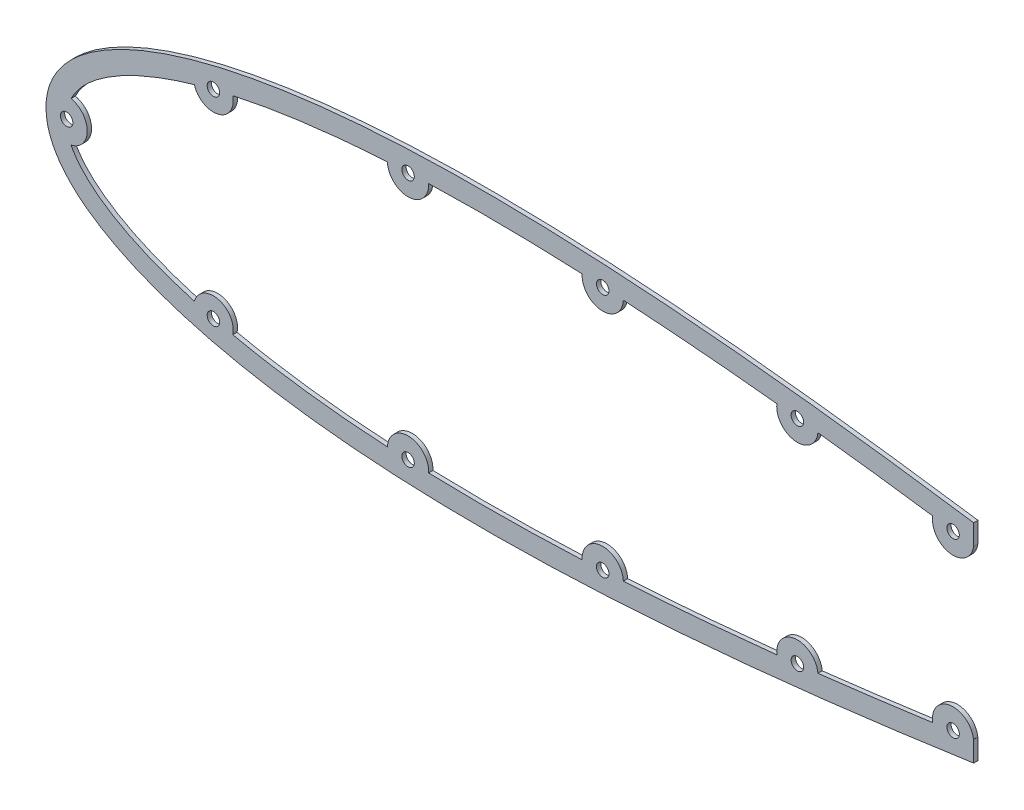
SolidWorks part; units mm, degrees
material "Silicon Rubber"
ref_plane "Front Plane" through (0, 0, 0) normal (0, 0, 1) x (1, 0, 0)
ref_plane "Top Plane" through (0, 0, 0) normal (0, 1, 0) x (1, 0, 0)
ref_plane "Right Plane" through (0, 0, 0) normal (1, 0, 0) x (0, 0, -1)
sketch "Sketch2" plane through (0, 0, 0) normal (0, 0, 1) x (1, 0, 0)
  line L0 (68.2014, -26.7339) -> (68.2014, -21.4783)
  line L1 (68.2014, -21.4783) -> (68.1599, -21.4844)
  line L2 (68.1599, 21.4844) -> (68.2014, 21.4783)
  line L3 (68.2014, 21.4783) -> (68.2014, 26.7339)
  line L6 (68.1014, 21.5941) -> (68.1014, 26.6475)
  line L7 (68.0724, 21.5983) -> (68.1014, 21.5941)
  line L8 (68.1014, -21.5941) -> (68.0724, -21.5983)
  line L12 (68.1014, -26.6475) -> (68.1014, -21.5941)
  line L13 (68.1014, 21.5941) -> (68.1014, 26.6475)
  line L14 (68.0724, 21.5983) -> (68.1014, 21.5941)
  line L16 (68.1014, -21.5941) -> (68.0724, -21.5983)
  line L18 (68.1014, -26.6475) -> (68.1014, -21.5941)
  circle A0 centre (62.9014, 22.1461) radius 1.6 construction
  circle A1 centre (22.9014, 27.2583) radius 1.6 construction
  circle A2 centre (-27.0986, 31.4546) radius 1.6 construction
  circle A3 centre (-77.0986, 31.8817) radius 1.6 construction
  circle A4 centre (-127.0986, 25.5249) radius 1.6 construction
  circle A5 centre (-164.8, 0) radius 1.6 construction
  circle A6 centre (-77.0986, -31.8817) radius 1.6 construction
  circle A7 centre (-27.0986, -31.4546) radius 1.6 construction
  circle A8 centre (22.9014, -27.2583) radius 1.6 construction
  circle A9 centre (62.9014, -22.1461) radius 1.6 construction
  circle A10 centre (-127.0986, -25.5249) radius 1.6 construction
  arc A11 (57.7843, 23.0714) -> (68.0724, 21.5983) centre (62.9014, 22.1461) ccw
  arc A12 (17.7571, 28.0176) -> (28.087, 26.8723) centre (22.9014, 27.2583) ccw
  arc A13 (-32.2789, 31.9078) -> (-21.8995, 31.3623) centre (-27.0986, 31.4546) ccw
  arc A14 (-82.2982, 31.8126) -> (-71.9139, 32.2795) centre (-77.0986, 31.8817) ccw
  arc A16 (-131.9264, 24.2269) -> (-122.2317, 26.6674) centre (-127.0986, 25.5249) ccw
  arc A18 (-163.7985, -5.1026) -> (-163.7985, 5.1026) centre (-164.8, 0) ccw
  arc A20 (-122.2317, -26.6674) -> (-131.9264, -24.2269) centre (-127.0986, -25.5249) ccw
  arc A22 (-71.9139, -32.2795) -> (-82.2982, -31.8126) centre (-77.0986, -31.8817) ccw
  arc A24 (-21.8995, -31.3623) -> (-32.2789, -31.9078) centre (-27.0986, -31.4546) ccw
  arc A39 (28.087, -26.8723) -> (17.7571, -28.0176) centre (22.9014, -27.2583) ccw
  arc A40 (68.0724, -21.5983) -> (57.7843, -23.0714) centre (62.9014, -22.1461) ccw
  arc A41 (57.7843, 23.0714) -> (68.0724, 21.5983) centre (62.9014, 22.1461) ccw
  arc A42 (17.7571, 28.0176) -> (28.087, 26.8723) centre (22.9014, 27.2583) ccw
  arc A43 (-32.2789, 31.9078) -> (-21.8995, 31.3623) centre (-27.0986, 31.4546) ccw
  arc A44 (-82.2982, 31.8126) -> (-71.9139, 32.2795) centre (-77.0986, 31.8817) ccw
  arc A45 (-131.9264, 24.2269) -> (-122.2317, 26.6674) centre (-127.0986, 25.5249) ccw
  arc A46 (-163.7985, -5.1026) -> (-163.7985, 5.1026) centre (-164.8, 0) ccw
  arc A47 (-122.2317, -26.6674) -> (-131.9264, -24.2269) centre (-127.0986, -25.5249) ccw
  arc A48 (-71.9139, -32.2795) -> (-82.2982, -31.8126) centre (-77.0986, -31.8817) ccw
  arc A49 (-21.8995, -31.3623) -> (-32.2789, -31.9078) centre (-27.0986, -31.4546) ccw
  arc A52 (28.087, -26.8723) -> (17.7571, -28.0176) centre (22.9014, -27.2583) ccw
  arc A54 (68.0724, -21.5983) -> (57.7843, -23.0714) centre (62.9014, -22.1461) ccw
  circle A56 centre (62.9014, 22.1461) radius 1.6
  circle A58 centre (22.9014, 27.2583) radius 1.6
  circle A60 centre (-27.0986, 31.4546) radius 1.6
  circle A65 centre (-77.0986, 31.8817) radius 1.6
  circle A66 centre (-127.0986, 25.5249) radius 1.6
  circle A67 centre (-164.8, 0) radius 1.6
  circle A68 centre (-77.0986, -31.8817) radius 1.6
  circle A69 centre (-27.0986, -31.4546) radius 1.6
  circle A70 centre (22.9014, -27.2583) radius 1.6
  circle A71 centre (62.9014, -22.1461) radius 1.6
  circle A72 centre (-127.0986, -25.5249) radius 1.6
  arc A73 (68.1599, -21.4844) -> (57.6684, -22.9866) centre (62.9014, -22.1461) ccw
  arc A74 (28.178, -26.7611) -> (17.644, -27.929) centre (22.9014, -27.2583) ccw
  arc A75 (-21.8024, -31.2563) -> (-32.3865, -31.8125) centre (-27.0986, -31.4546) ccw
  arc A76 (-71.8072, -32.1828) -> (-82.3958, -31.7067) centre (-77.0986, -31.8817) ccw
  arc A77 (-122.1122, -26.5912) -> (-131.9956, -24.1029) centre (-127.0986, -25.5249) ccw
  arc A78 (-163.6523, -5.1742) -> (-163.6523, 5.1742) centre (-164.8, 0) ccw
  arc A79 (-131.9956, 24.1029) -> (-122.1122, 26.5912) centre (-127.0986, 25.5249) ccw
  arc A80 (-82.3958, 31.7067) -> (-71.8072, 32.1828) centre (-77.0986, 31.8817) ccw
  arc A105 (-32.3865, 31.8125) -> (-21.8024, 31.2563) centre (-27.0986, 31.4546) ccw
  arc A106 (17.644, 27.929) -> (28.178, 26.7611) centre (22.9014, 27.2583) ccw
  arc A107 (57.6684, 22.9866) -> (68.1599, 21.4844) centre (62.9014, 22.1461) ccw
  spline S0 degree 1 poles (68.2014, 26.7339) (-170.1, 0) knots 0 0 1 1 construction
  spline S1 degree 1 poles (-170.1, 0) (68.2014, -26.7339) knots 0 0 1 1 construction
  spline S2 degree 1 poles (57.6684, -22.9866) (28.178, -26.7611) knots 0 0 1 1 construction
  spline S3 degree 1 poles (17.644, -27.929) (-21.8024, -31.2563) knots 0 0 1 1 construction
  spline S4 degree 1 poles (-32.3865, -31.8125) (-71.8072, -32.1828) knots 0 0 1 1 construction
  spline S5 degree 1 poles (-82.3958, -31.7067) (-122.1122, -26.5912) knots 0 0 1 1 construction
  spline S6 degree 1 poles (-131.9956, -24.1029) (-163.6523, -5.1742) knots 0 0 1 1 construction
  spline S7 degree 1 poles (-163.6523, 5.1742) (-131.9956, 24.1029) knots 0 0 1 1 construction
  spline S8 degree 1 poles (-122.1122, 26.5912) (-82.3958, 31.7067) knots 0 0 1 1 construction
  spline S9 degree 1 poles (-71.8072, 32.1828) (-32.3865, 31.8125) knots 0 0 1 1 construction
  spline S10 degree 1 poles (-21.8024, 31.2563) (17.644, 27.929) knots 0 0 1 1 construction
  spline S11 degree 1 poles (28.178, 26.7611) (57.6684, 22.9866) knots 0 0 1 1 construction
  spline S13 degree 3 poles (-842.1181, -1671.7155) (-666.8136, -29.7436) (-299.6609, 70.7294) (451.6225, -29.366) (859.6621, -263.4671) (-1750.034, 876.0193) knots -3.144259 -3.144259 -3.144259 -3.144259 0.860716 0.922196 5.547029 5.547029 5.547029 5.547029 only from (28.087, 26.8723) to (57.7843, 23.0714)
  spline S14 degree 3 poles (-801.262, -1742.9904) (-608.4086, -55.3942) (138.9892, 217.5077) (846.5588, -333.1109) (874.3091, 1643.1183) knots -2.784932 -2.784932 -2.784932 -2.784932 0.737757 5.645129 5.645129 5.645129 5.645129 only from (-21.8995, 31.3623) to (17.7571, 28.0176)
  spline S15 degree 3 poles (-291.0162, -1916.8032) (-507.1608, -118.9354) (34.6459, 253.136) (621.4934, -288.9416) (405.8213, 1893.2388) knots -2.162015 -2.162015 -2.162015 -2.162015 0.491838 4.302613 4.302613 4.302613 4.302613 only from (-71.9139, 32.2795) to (-32.2789, 31.9078)
  spline S16 degree 3 poles (741.1533, -1760.707) (-343.2115, -150.34) (-241.253, 13.975) (186.8439, 63.9274) (527.7556, -277.064) (56.5333, 1961.8797) knots -1.314597 -1.314597 -1.314597 -1.314597 0.245919 0.368878 3.687915 3.687915 3.687915 3.687915 only from (-122.2317, 26.6674) to (-82.2982, 31.8126)
  spline S17 degree 3 poles (1723.4477, -655.8326) (258.0308, -164.7434) (-207.3618, -48.8694) (-159.9742, 10.6557) (-154.2388, 14.9829) (-147.6638, 18.5471) (-140.6029, 21.4867) (12.7833, 72.1997) (283.1196, -141.398) (-1275.2751, 1653.5581) knots -0.974835 -0.974835 -0.974835 -0.974835 0.03074 0.06148 0.09222 0.122959 0.153699 0.184439 2.046029 2.046029 2.046029 2.046029 only from (-163.7985, 5.1026) to (-131.9264, 24.2269)
  spline S18 degree 3 poles (-1275.2616, -1653.5425) (283.118, 141.3968) (12.7829, -72.1996) (-140.6029, -21.4867) (-147.6638, -18.5471) (-154.2388, -14.9829) (-159.9742, -10.6557) (-207.3614, 48.8689) (258.0229, 164.7415) (1723.4095, 655.8198) knots -1.062348 -1.062348 -1.062348 -1.062348 0.799237 0.829976 0.860716 0.891456 0.922196 0.952936 1.958502 1.958502 1.958502 1.958502 only from (-131.9264, -24.2269) to (-163.7985, -5.1026)
  spline S19 degree 3 poles (56.5306, -1961.8927) (527.7568, 277.0653) (186.8444, -63.9275) (-241.253, -13.975) (-343.2116, 150.34) (741.1538, 1760.7078) knots -2.704246 -2.704246 -2.704246 -2.704246 0.614797 0.737757 2.298273 2.298273 2.298273 2.298273 only from (-82.2982, -31.8126) to (-122.2317, -26.6674)
  spline S20 degree 3 poles (405.8239, -1893.2123) (621.4906, 288.939) (34.6482, -253.1318) (-507.1541, 118.9308) (-291.0259, 1916.7219) knots -3.318922 -3.318922 -3.318922 -3.318922 0.491838 3.145651 3.145651 3.145651 3.145651 only from (-32.2789, -31.9078) to (-71.9139, -32.2795)
  spline S21 degree 3 poles (874.3087, -1643.0904) (846.555, 333.1079) (138.9897, -217.5049) (-608.4031, 55.3922) (-801.257, 1742.9458) knots -4.66143 -4.66143 -4.66143 -4.66143 0.245919 3.768577 3.768577 3.768577 3.768577 only from (17.7571, -28.0176) to (-21.8995, -31.3623)
  spline S22 degree 3 poles (-1750.0783, -876.0387) (859.6666, 263.4697) (451.6248, 29.3663) (-299.6602, -70.7293) (-666.8122, 29.7432) (-842.1171, 1671.7055) knots -4.563379 -4.563379 -4.563379 -4.563379 0.06148 0.122959 4.127926 4.127926 4.127926 4.127926 only from (57.7843, -23.0714) to (28.087, -26.8723)
  spline S23 degree 3 poles (708.7122, -1786.7537) (26.0228, 147.1611) (-186.9064, 41.2677) (-168.2655, -7.6563) (-166.1256, -10.9895) (-163.4817, -13.9306) (-160.4992, -16.5204) (-156.2088, -19.5733) (-150.4451, -22.7629) (-143.1818, -25.8606) (-135.7072, -28.4002) (-128.0976, -30.4933) (-120.3969, -32.2192) (-112.6334, -33.6326) (-104.8261, -34.778) (-96.9881, -35.6886) (-89.1288, -36.3914) (-81.2552, -36.9087) (-73.3723, -37.259) (-65.4842, -37.4585) (-57.5937, -37.5209) (-49.7032, -37.4581) (-39.1846, -37.2223) (-26.0439, -36.6653) (-10.2939, -35.6417) (5.4338, -34.3131) (21.1378, -32.722) (36.8174, -30.901) (531.6613, 33.0393) (986.8564, 360.6878) (1492.0432, -1113.8011) knots -0.00686 -0.00686 -0.00686 -0.00686 0.369162 0.379176 0.389189 0.399202 0.409216 0.419229 0.439256 0.459282 0.479309 0.499335 0.519362 0.539388 0.559415 0.579442 0.599468 0.619495 0.639521 0.659548 0.679575 0.699601 0.719628 0.759681 0.799734 0.839787 0.879841 0.919894 0.959947 4.677847 4.677847 4.677847 4.677847 only from (-170, 0) to (68.1014, -26.6475)
  spline S24 degree 3 poles (1492.0395, 1113.7903) (986.8542, -360.6862) (531.6601, -33.0392) (36.8174, 30.901) (21.1378, 32.722) (5.4338, 34.3131) (-10.2939, 35.6417) (-26.0439, 36.6653) (-39.1846, 37.2223) (-49.7032, 37.4581) (-57.5937, 37.5209) (-65.4842, 37.4585) (-73.3723, 37.259) (-81.2552, 36.9087) (-89.1288, 36.3914) (-96.9881, 35.6886) (-104.8261, 34.778) (-112.6334, 33.6326) (-120.3969, 32.2192) (-128.0976, 30.4933) (-135.7072, 28.4002) (-143.1818, 25.8606) (-150.4451, 22.7629) (-156.2088, 19.5733) (-160.4992, 16.5204) (-163.4817, 13.9306) (-166.1256, 10.9895) (-168.2655, 7.6563) (-186.9051, -41.2643) (25.9921, -147.1458) (708.5607, 1786.3244) knots -3.318689 -3.318689 -3.318689 -3.318689 0.399202 0.439255 0.479309 0.519362 0.559415 0.599468 0.639521 0.659548 0.679575 0.699601 0.719628 0.739654 0.759681 0.779707 0.799734 0.819761 0.839787 0.859814 0.87984 0.899867 0.919894 0.93992 0.949934 0.959947 0.96996 0.979973 0.989987 1.365981 1.365981 1.365981 1.365981 only from (68.1014, 26.6475) to (-170, 0)
  spline S25 degree 3 poles (28.087, 26.8723) (32.4652, 26.366) (42.1622, 25.1875) (52.0547, 23.8695) (57.577, 23.1003) (57.7843, 23.0714) knots 0.810152 0.810152 0.810152 0.810152 0.860716 0.922196 0.924595 0.924595 0.924595 0.924595
  spline S26 degree 3 poles (-21.8995, 31.3623) (-11.5048, 30.739) (1.7185, 29.6628) (14.9288, 28.3173) (17.7571, 28.0176) knots 0.617971 0.617971 0.617971 0.617971 0.737757 0.770399 0.770399 0.770399 0.770399
  spline S27 degree 3 poles (-71.9139, 32.2795) (-66.1939, 32.4615) (-52.9919, 32.6066) (-39.7649, 32.2434) (-32.2789, 31.9078) knots 0.425655 0.425655 0.425655 0.425655 0.491838 0.578103 0.578103 0.578103 0.578103
  spline S28 degree 3 poles (-122.2317, 26.6674) (-120.8288, 26.9751) (-109.1533, 29.389) (-95.7605, 30.9517) (-83.735, 31.7283) (-82.2982, 31.8126) knots 0.22905 0.22905 0.22905 0.22905 0.245919 0.368878 0.385551 0.385551 0.385551 0.385551
  spline S29 degree 3 poles (-163.7985, 5.1026) (-163.7409, 5.2221) (-162.7964, 7.1106) (-159.9742, 10.6557) (-154.2388, 14.9829) (-147.6638, 18.5471) (-140.6029, 21.4867) (-135.2757, 23.248) (-132.3571, 24.103) (-131.9264, 24.2269) knots 0.028669 0.028669 0.028669 0.028669 0.03074 0.06148 0.09222 0.122959 0.153699 0.184439 0.189748 0.189748 0.189748 0.189748
  spline S30 degree 3 poles (-131.9264, -24.2269) (-132.3571, -24.103) (-135.2757, -23.248) (-140.6029, -21.4867) (-147.6638, -18.5471) (-154.2388, -14.9829) (-159.9742, -10.6557) (-162.7964, -7.1106) (-163.7409, -5.2221) (-163.7985, -5.1026) knots 0.793928 0.793928 0.793928 0.793928 0.799237 0.829976 0.860716 0.891456 0.922196 0.952936 0.955007 0.955007 0.955007 0.955007
  spline S31 degree 3 poles (-82.2982, -31.8126) (-83.735, -31.7283) (-95.7605, -30.9517) (-109.1533, -29.389) (-120.8288, -26.9751) (-122.2317, -26.6674) knots 0.598125 0.598125 0.598125 0.598125 0.614797 0.737757 0.754626 0.754626 0.754626 0.754626
  spline S32 degree 3 poles (-32.2789, -31.9078) (-39.7649, -32.2434) (-52.9919, -32.6066) (-66.1939, -32.4615) (-71.9139, -32.2795) knots 0.405573 0.405573 0.405573 0.405573 0.491838 0.558021 0.558021 0.558021 0.558021
  spline S33 degree 3 poles (17.7571, -28.0176) (14.9288, -28.3173) (1.7185, -29.6628) (-11.5048, -30.739) (-21.8995, -31.3623) knots 0.213277 0.213277 0.213277 0.213277 0.245919 0.365705 0.365705 0.365705 0.365705
  spline S34 degree 3 poles (57.7843, -23.0714) (57.577, -23.1003) (52.0547, -23.8695) (42.1622, -25.1875) (32.4652, -26.366) (28.087, -26.8723) knots 0.059081 0.059081 0.059081 0.059081 0.06148 0.122959 0.173523 0.173523 0.173523 0.173523
  spline S35 degree 3 poles (-170, 0) (-170, -1.3149) (-169.6794, -3.9455) (-168.2655, -7.6563) (-166.1256, -10.9895) (-163.4817, -13.9306) (-160.4992, -16.5204) (-156.2088, -19.5733) (-150.4451, -22.7629) (-143.1818, -25.8606) (-135.7072, -28.4002) (-128.0976, -30.4933) (-120.3969, -32.2192) (-112.6334, -33.6326) (-104.8261, -34.778) (-96.9881, -35.6886) (-89.1288, -36.3914) (-81.2552, -36.9087) (-73.3723, -37.259) (-65.4842, -37.4585) (-57.5937, -37.5209) (-49.7032, -37.4581) (-39.1846, -37.2223) (-26.0439, -36.6653) (-10.2939, -35.6417) (5.4338, -34.3131) (21.1378, -32.722) (36.8174, -30.901) (52.473, -28.8781) (62.8944, -27.4093) (68.1014, -26.6475) knots 0.359149 0.359149 0.359149 0.359149 0.369162 0.379176 0.389189 0.399202 0.409216 0.419229 0.439256 0.459282 0.479309 0.499335 0.519362 0.539388 0.559415 0.579442 0.599468 0.619495 0.639521 0.659548 0.679575 0.699601 0.719628 0.759681 0.799734 0.839787 0.879841 0.919894 0.959947 1 1 1 1
  spline S36 degree 3 poles (68.1014, 26.6475) (62.8944, 27.4093) (52.473, 28.8781) (36.8174, 30.901) (21.1378, 32.722) (5.4338, 34.3131) (-10.2939, 35.6417) (-26.0439, 36.6653) (-39.1846, 37.2223) (-49.7032, 37.4581) (-57.5937, 37.5209) (-65.4842, 37.4585) (-73.3723, 37.259) (-81.2552, 36.9087) (-89.1288, 36.3914) (-96.9881, 35.6886) (-104.8261, 34.778) (-112.6334, 33.6326) (-120.3969, 32.2192) (-128.0976, 30.4933) (-135.7072, 28.4002) (-143.1818, 25.8606) (-150.4451, 22.7629) (-156.2088, 19.5733) (-160.4992, 16.5204) (-163.4817, 13.9306) (-166.1256, 10.9895) (-168.2655, 7.6563) (-169.6794, 3.9455) (-170, 1.3149) (-170, 0) knots 0.359149 0.359149 0.359149 0.359149 0.399202 0.439255 0.479309 0.519362 0.559415 0.599468 0.639521 0.659548 0.679575 0.699601 0.719628 0.739654 0.759681 0.779707 0.799734 0.819761 0.839787 0.859814 0.87984 0.899867 0.919894 0.93992 0.949934 0.959947 0.96996 0.979973 0.989987 1 1 1 1
  spline S37 degree 3 poles (68.2014, 26.7339) (57.7842, 28.2587) (36.9164, 31.0912) (5.5199, 34.5371) (-25.9743, 36.9377) (-52.2868, 37.7649) (-73.3405, 37.4356) (-89.1109, 36.5858) (-104.827, 34.9972) (-120.4245, 32.4744) (-133.2256, 29.3469) (-143.2047, 25.9592) (-150.4792, 22.8584) (-157.4074, 19.0226) (-163.7078, 14.1892) (-167.8769, 8.9513) (-169.7776, 3.9723) (-170.1, 1.3203) (-170.1, 0) knots 0.35893 0.35893 0.35893 0.35893 0.439064 0.519197 0.599331 0.679465 0.719532 0.759599 0.799666 0.839732 0.879799 0.899833 0.919866 0.9399 0.959933 0.979967 0.989983 1 1 1 1
  spline S38 degree 3 poles (-170.1, 0) (-170.1, -1.3203) (-169.7776, -3.9723) (-167.8769, -8.9513) (-163.7078, -14.1892) (-157.4074, -19.0226) (-150.4792, -22.8584) (-143.2047, -25.9592) (-133.2256, -29.3469) (-120.4245, -32.4744) (-104.827, -34.9972) (-89.1109, -36.5858) (-73.3405, -37.4356) (-52.2868, -37.7649) (-25.9743, -36.9377) (5.5199, -34.5371) (36.9164, -31.0912) (57.7842, -28.2587) (68.2014, -26.7339) knots 0.359149 0.359149 0.359149 0.359149 0.369166 0.379183 0.399216 0.419249 0.439283 0.459316 0.47935 0.519417 0.559484 0.59955 0.639617 0.679684 0.759818 0.839952 0.920086 1.000219 1.000219 1.000219 1.000219
  spline S39 degree 3 poles (57.6684, -22.9866) (47.853, -24.3552) (38.0226, -25.6218) (28.178, -26.7611) knots 0.059475 0.059475 0.059475 0.059475 0.173129 0.173129 0.173129 0.173129
  spline S40 degree 3 poles (17.644, -27.929) (11.0786, -28.6241) (-2.0732, -29.8921) (-15.2199, -30.8607) (-21.8024, -31.2563) knots 0.213672 0.213672 0.213672 0.213672 0.28949 0.365309 0.365309 0.365309 0.365309
  spline S41 degree 3 poles (-32.3865, -31.8125) (-38.9591, -32.1061) (-52.129, -32.4924) (-65.2464, -32.3899) (-71.8072, -32.1828) knots 0.405969 0.405969 0.405969 0.405969 0.481795 0.557621 0.557621 0.557621 0.557621
  spline S42 degree 3 poles (-82.3958, -31.7067) (-89.0879, -31.3122) (-99.14, -30.451) (-112.3507, -28.5429) (-118.8681, -27.3009) (-122.1122, -26.5912) knots 0.598525 0.598525 0.598525 0.598525 0.676379 0.715306 0.754233 0.754233 0.754233 0.754233
  spline S43 degree 3 poles (-131.9956, -24.1029) (-133.612, -23.6367) (-136.836, -22.6426) (-143.1302, -20.3994) (-149.1682, -17.7147) (-154.68, -14.4537) (-157.8042, -12.1461) (-159.9985, -10.1307) (-161.4619, -8.5392) (-162.7125, -6.8734) (-163.3625, -5.7613) (-163.6523, -5.1742) knots 0.794326 0.794326 0.794326 0.794326 0.814327 0.834329 0.874331 0.894333 0.914334 0.924335 0.934335 0.944336 0.954337 0.954337 0.954337 0.954337
  spline S44 degree 3 poles (-163.6523, 5.1742) (-163.3625, 5.7613) (-162.7125, 6.8734) (-161.4619, 8.5392) (-159.9985, 10.1307) (-157.8042, 12.1461) (-154.68, 14.4537) (-149.1682, 17.7147) (-143.1302, 20.3994) (-136.836, 22.6426) (-133.612, 23.6367) (-131.9956, 24.1029) knots 0.029339 0.029339 0.029339 0.029339 0.03934 0.049341 0.059341 0.069342 0.089343 0.109345 0.149347 0.169349 0.18935 0.18935 0.18935 0.18935
  spline S45 degree 3 poles (-122.1122, 26.5912) (-118.8681, 27.3009) (-112.3507, 28.5429) (-99.14, 30.451) (-89.0879, 31.3122) (-82.3958, 31.7067) knots 0.229443 0.229443 0.229443 0.229443 0.26837 0.307297 0.385151 0.385151 0.385151 0.385151
  spline S46 degree 3 poles (-71.8072, 32.1828) (-65.2464, 32.3899) (-52.129, 32.4924) (-38.9591, 32.1061) (-32.3865, 31.8125) knots 0.426054 0.426054 0.426054 0.426054 0.50188 0.577706 0.577706 0.577706 0.577706
  spline S47 degree 3 poles (-21.8024, 31.2563) (-15.2199, 30.8607) (-2.0732, 29.8921) (11.0786, 28.6241) (17.644, 27.929) knots 0.618367 0.618367 0.618367 0.618367 0.694186 0.770004 0.770004 0.770004 0.770004
  spline S48 degree 3 poles (28.178, 26.7611) (38.0226, 25.6218) (47.853, 24.3552) (57.6684, 22.9866) knots 0.810547 0.810547 0.810547 0.810547 0.924201 0.924201 0.924201 0.924201
  dimension "D1" = 0
  dimension "D2" = 0.1
extrude "Boss-Extrude1" add sketch "Sketch2" along normal blind 0.5 and the other way blind 0.6 contours A106 S48 A107 L2 L3 S37 S38 L0 L1 A73 S39 A74 S40 A75 S41 A76 S42 A77 S43 A78 S44 A79 S45 A80 S46 A105 S47 S36 L13 L14 A41 S25 A42 S26 A43 S27 A44 S28 A45 S29 A46 S30 A47 S31 A48 S32 A49 S33 A52 S34 | L13 S36 S35 L18 L16 A54 S34 A52 S33 A49 S32 A48 S31 A47 S30 A46 S29 A45 S28 A44 S27 A43 S26 A42 S25 A41 L14 A56 A58 A60 A65 A66 A67 A68 A69 A70 A71 A72
